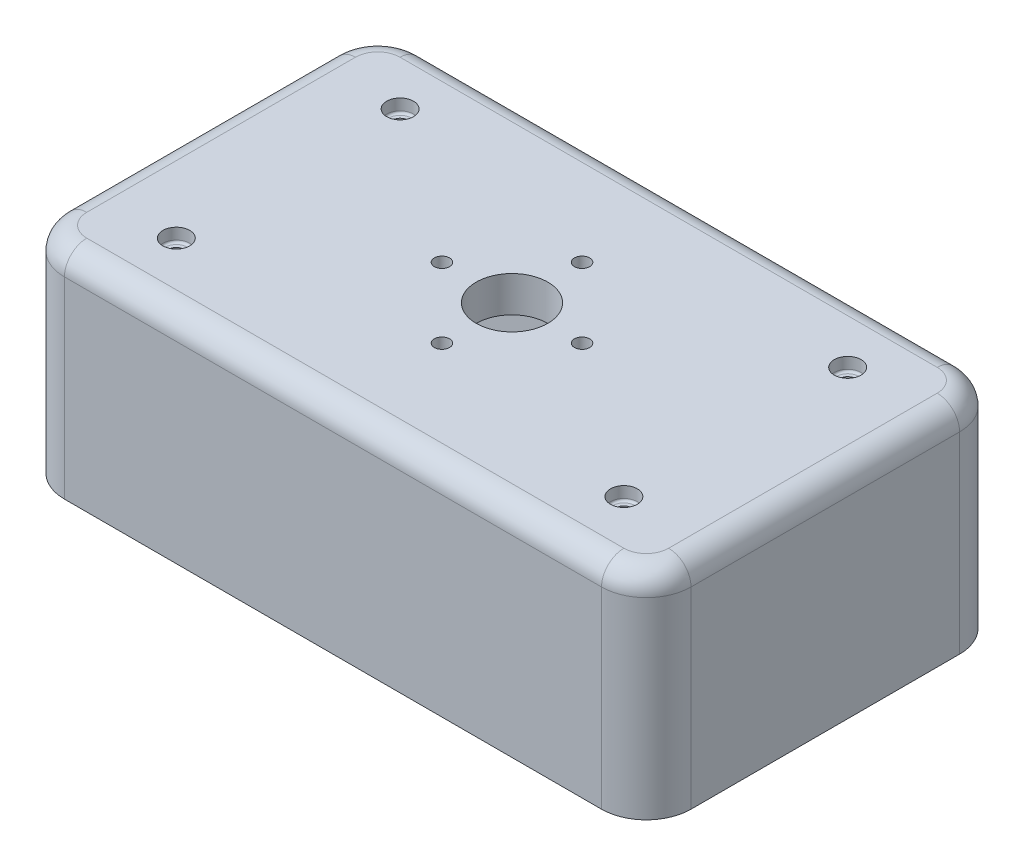
SolidWorks part; units mm, degrees
ref_plane "Front Plane" through (0, 0, 0) normal (0, 0, 1) x (1, 0, 0)
ref_plane "Top Plane" through (0, 0, 0) normal (0, 1, 0) x (1, 0, 0)
ref_plane "Right Plane" through (0, 0, 0) normal (1, 0, 0) x (0, 0, -1)
sketch "Sketch1" plane through (0, 0, 0) normal (0, 1, 0) x (1, 0, 0)
  line L1 (-70, -40) -> (70, -40)
  line L2 (-70, -40) -> (-70, 40)
  line L3 (-70, 40) -> (70, 40)
  line L4 (70, -40) -> (70, 40)
  line L5 (-70, -40) -> (70, 40) construction
  line L6 (-70, 40) -> (70, -40) construction
  point P0 (0, 0)
  dimension "D1" = 80
  dimension "D2" = 140
extrude "Boss-Extrude1" add sketch "Sketch1" along normal blind 48
fillet "Fillet1" radius 10 4 edges at (-70, 24, -40) (70, 24, -40) (70, 24, 40) (-70, 24, 40)
fillet "Fillet2" radius 5 8 edges at (67.0711, 48, -37.0711) (70, 48, 0) (67.0711, 48, 37.0711) (0, 48, 40) (-67.0711, 48, 37.0711) (-70, 48, 0) (-67.0711, 48, -37.0711) (0, 48, -40)
sketch "Sketch2" plane through (0, 0, 0) normal (0, -1, 0) x (1, 0, 0)
  line L1 (-55, -35) -> (55, -35)
  line L2 (-65, -25) -> (-65, 25)
  line L3 (-55, 35) -> (55, 35)
  line L4 (65, -25) -> (65, 25)
  line L5 (-65, -35) -> (65, 35) construction
  line L6 (-65, 35) -> (65, -35) construction
  arc A0 (-65, 25) -> (-55, 35) centre (-55, 25) cw
  arc A1 (-55, -35) -> (-65, -25) centre (-55, -25) cw
  arc A2 (65, -25) -> (55, -35) centre (55, -25) cw
  arc A3 (65, 25) -> (55, 35) centre (55, 25) ccw
  point P0 (0, 0)
  dimension "D3" = 10
  dimension "D1" = 70
  dimension "D2" = 130
extrude "Cut-Extrude1" cut sketch "Sketch2" against normal blind 40
sketch "Sketch3" plane through (0, 40, 0) normal (0, -1, 0) x (-1, 0, 0)
  line L1 (50, 25) -> (-50, 25) construction
  line L2 (50, 25) -> (50, -25) construction
  line L3 (50, -25) -> (-50, -25) construction
  line L4 (-50, 25) -> (-50, -25) construction
  line L5 (50, 25) -> (-50, -25) construction
  line L6 (50, -25) -> (-50, 25) construction
  circle A0 centre (50, -25) radius 3.7
  circle A1 centre (-50, -25) radius 3.7
  circle A2 centre (50, 25) radius 3.7
  circle A3 centre (-50, 25) radius 3.7
  point P0 (0, 0)
  dimension "D1" = 50
  dimension "D2" = 100
extrude "Boss-Extrude2" add sketch "Sketch3" along normal blind 40
sketch "Sketch5" plane through (0, 0, 0) normal (0, -1, 0) x (-1, 0, 0)
  circle A0 centre (50, -25) radius 1.7
  circle A1 centre (-50, -25) radius 1.7
  circle A2 centre (50, 25) radius 1.7
  circle A3 centre (-50, 25) radius 1.7
extrude "Cut-Extrude4" cut sketch "Sketch5" against normal through all
sketch "Sketch6" plane through (0, 48, 0) normal (0, 1, 0) x (1, 0, 0)
  circle A0 centre (-50, 25) radius 3
  circle A1 centre (50, 25) radius 3
  circle A2 centre (-50, -25) radius 3
  circle A3 centre (50, -25) radius 3
extrude "Cut-Extrude5" cut sketch "Sketch6" against normal blind 3
fillet "Fillet3" radius 0.5 4 edges at (50, 45, -22) (50, 45, 28) (-50, 45, -22) (-50, 45, 28)
fillet "Fillet4" radius 2 8 edges at (-62.0711, 40, -32.0711) (-65, 40, 0) (-62.0711, 40, 32.0711) (0, 40, 35) (62.0711, 40, 32.0711) (65, 40, 0) (62.0711, 40, -32.0711) (0, 40, -35)
fillet "Fillet5" radius 1 4 edges at (-50, 40, 28.7) (-50, 40, -21.3) (50, 40, 28.7) (50, 40, -21.3)
sketch "Sketch7" plane through (0, 48, 0) normal (0, 1, 0) x (1, 0, 0)
  circle A0 centre (0, 0) radius 8
extrude "Cut-Extrude6" cut sketch "Sketch7" against normal through all
sketch "Sketch8" plane through (0, 48, 0) normal (0, 1, 0) x (1, 0, 0)
  circle A0 centre (0, 0) radius 15.65 construction
  circle A1 centre (0, 15.65) radius 1.7
  circle A2 centre (15.65, 0) radius 1.7
  circle A3 centre (0, -15.65) radius 1.7
  circle A4 centre (-15.65, 0) radius 1.7
extrude "Cut-Extrude7" cut sketch "Sketch8" against normal through all
sketch "Sketch9" plane through (0, 40, 0) normal (0, -1, 0) x (1, 0, 0)
  line L1 (3, 15.65) -> (1.5, 18.2481)
  line L2 (1.5, 18.2481) -> (-1.5, 18.2481)
  line L3 (-1.5, 18.2481) -> (-3, 15.65)
  line L4 (-3, 15.65) -> (-1.5, 13.0519)
  line L5 (-1.5, 13.0519) -> (1.5, 13.0519)
  line L6 (1.5, 13.0519) -> (3, 15.65)
  line L7 (18.65, 0) -> (17.15, 2.5981)
  line L8 (17.15, 2.5981) -> (14.15, 2.5981)
  line L9 (14.15, 2.5981) -> (12.65, 0)
  line L10 (12.65, 0) -> (14.15, -2.5981)
  line L11 (14.15, -2.5981) -> (17.15, -2.5981)
  line L12 (17.15, -2.5981) -> (18.65, 0)
  line L13 (3, -15.65) -> (1.5, -13.0519)
  line L14 (1.5, -13.0519) -> (-1.5, -13.0519)
  line L15 (-1.5, -13.0519) -> (-3, -15.65)
  line L16 (-3, -15.65) -> (-1.5, -18.2481)
  line L17 (-1.5, -18.2481) -> (1.5, -18.2481)
  line L18 (1.5, -18.2481) -> (3, -15.65)
  line L19 (-12.65, 0) -> (-14.15, 2.5981)
  line L20 (-14.15, 2.5981) -> (-17.15, 2.5981)
  line L21 (-17.15, 2.5981) -> (-18.65, 0)
  line L22 (-18.65, 0) -> (-17.15, -2.5981)
  line L23 (-17.15, -2.5981) -> (-14.15, -2.5981)
  line L24 (-14.15, -2.5981) -> (-12.65, 0)
  circle A0 centre (0, 15.65) radius 2.5981 construction
  circle A1 centre (15.65, 0) radius 2.5981 construction
  circle A2 centre (0, -15.65) radius 2.5981 construction
  circle A3 centre (-15.65, 0) radius 2.5981 construction
  dimension "D1" = 3
  dimension "D2" = 3
  dimension "D3" = 3
  dimension "D4" = 3
extrude "Cut-Extrude8" cut sketch "Sketch9" against normal blind 2.7
